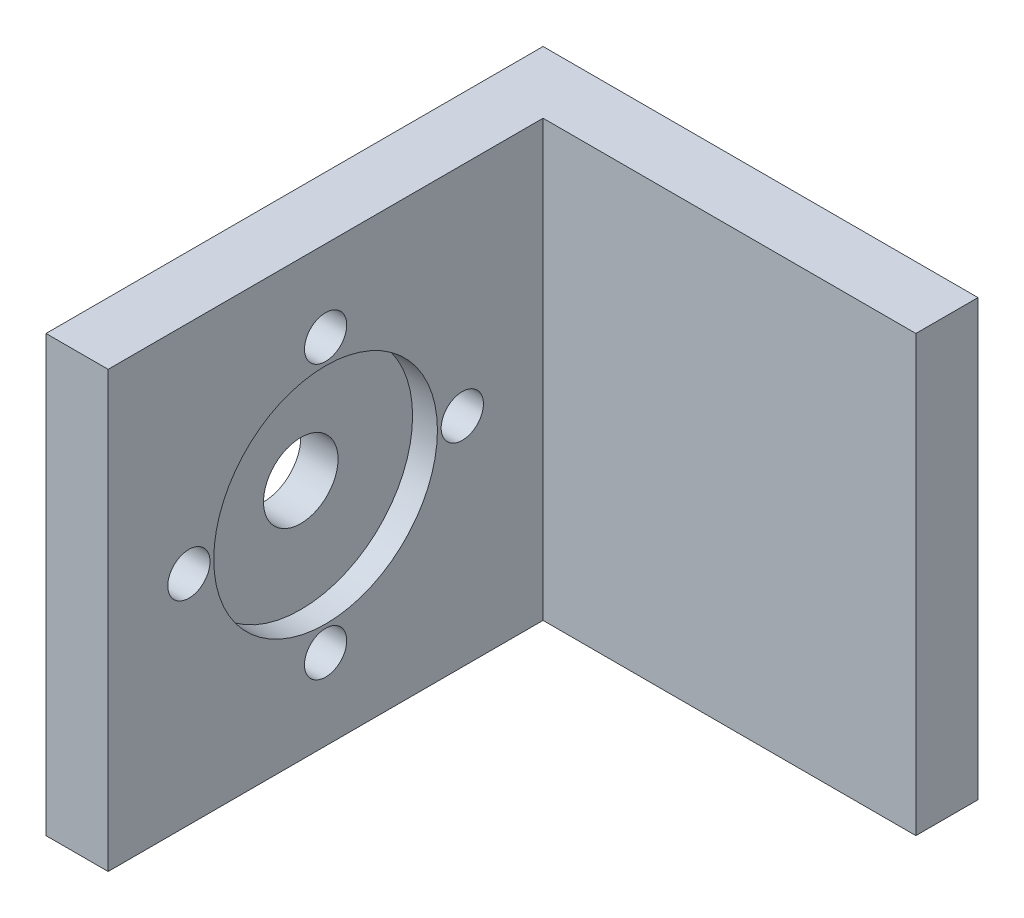
SolidWorks part; units mm, degrees
material "ABS"
ref_plane "Front Plane" through (0, 0, 0) normal (1, 0, 0) x (0, 1, 0)
ref_plane "Top Plane" through (0, 0, 0) normal (0, 0, 1) x (0, 1, 0)
ref_plane "Right Plane" through (0, 0, 0) normal (0, 1, 0) x (-1, 0, 0)
sketch "Sketch3" plane through (0, 0, 0) normal (1, 0, 0) x (0, 1, 0)
  line L1 (-17.5, -17.5) -> (17.5, -17.5)
  line L2 (-17.5, -17.5) -> (-17.5, 17.5)
  line L3 (-17.5, 17.5) -> (17.5, 17.5)
  line L4 (17.5, -17.5) -> (17.5, 17.5)
  line L5 (-17.5, -17.5) -> (17.5, 17.5) construction
  line L6 (-17.5, 17.5) -> (17.5, -17.5) construction
  point P0 (0, 0)
  dimension "D1" = 35
  dimension "D2" = 35
extrude "Boss-Extrude1" add sketch "Sketch3" along normal blind 5
sketch "Sketch4" plane through (5, 0, 0) normal (1, 0, 0) x (0, 1, 0)
  circle A0 centre (0, 0) radius 9
  dimension "D1" = 18
extrude "Cut-Extrude1" cut sketch "Sketch4" against normal blind 2
sketch "Sketch5" plane through (3, 0, 0) normal (1, 0, 0) x (0, 1, 0)
  circle A0 centre (0, 0) radius 3
  dimension "D1" = 6
extrude "Cut-Extrude2" cut sketch "Sketch5" against normal through all
sketch "Sketch6" plane through (5, 0, 0) normal (1, 0, 0) x (0, 1, 0)
  circle A0 centre (0, 0) radius 11 construction
  circle A1 centre (0, 11) radius 1.7
  circle A2 centre (-11, 0) radius 1.7
  circle A3 centre (0, -11) radius 1.7
  circle A4 centre (11, 0) radius 1.7
  point P3 (0, 11)
  point P4 (0, -11)
  point P5 (-11, 0)
  point P6 (11, 0)
  dimension "D1" = 22
  dimension "D2" = 3.4
  dimension "D3" = 3.4
  dimension "D4" = 3.4
  dimension "D5" = 3.4
extrude "Cut-Extrude3" cut sketch "Sketch6" against normal through all
sketch "Sketch8" plane through (0, 0, -17.5) normal (0, 0, -1) x (1, 0, 0)
  line L0 (0, 17.5) -> (0, -17.5)
  line L1 (0, 17.5) -> (35, 17.5)
  line L2 (0, -17.5) -> (35, -17.5)
  line L3 (35, 17.5) -> (35, -17.5)
  dimension "D1" = 35
extrude "Boss-Extrude2" add sketch "Sketch8" along normal blind 5
equation "\"L\"= 35mm'Length"
equation "\"b\"= 35mm'Width"
equation "\"h\"= 5mm'Depth"
equation "\"CH\"= 3.4mm'Clearance Hole"
equation "\"MC\"= 18mm'Motor Cutout"
equation "\"MA\"= 6mm'Motor Axle Hole"
equation "\"D1@Sketch3\"=\"L\""
equation "\"D2@Sketch3\"=\"b\""
equation "\"D1@Boss-Extrude1\"=\"h\""
equation "\"D1@Sketch4\"=\"MC\""
equation "\"D1@Sketch5\"=\"MA\""
equation "\"D2@Sketch6\"=\"CH\""
equation "\"D3@Sketch6\"=\"CH\""
equation "\"D5@Sketch6\"=\"CH\""
equation "\"D4@Sketch6\"=\"CH\""
equation "\"D1@Sketch8\"=\"L\""
